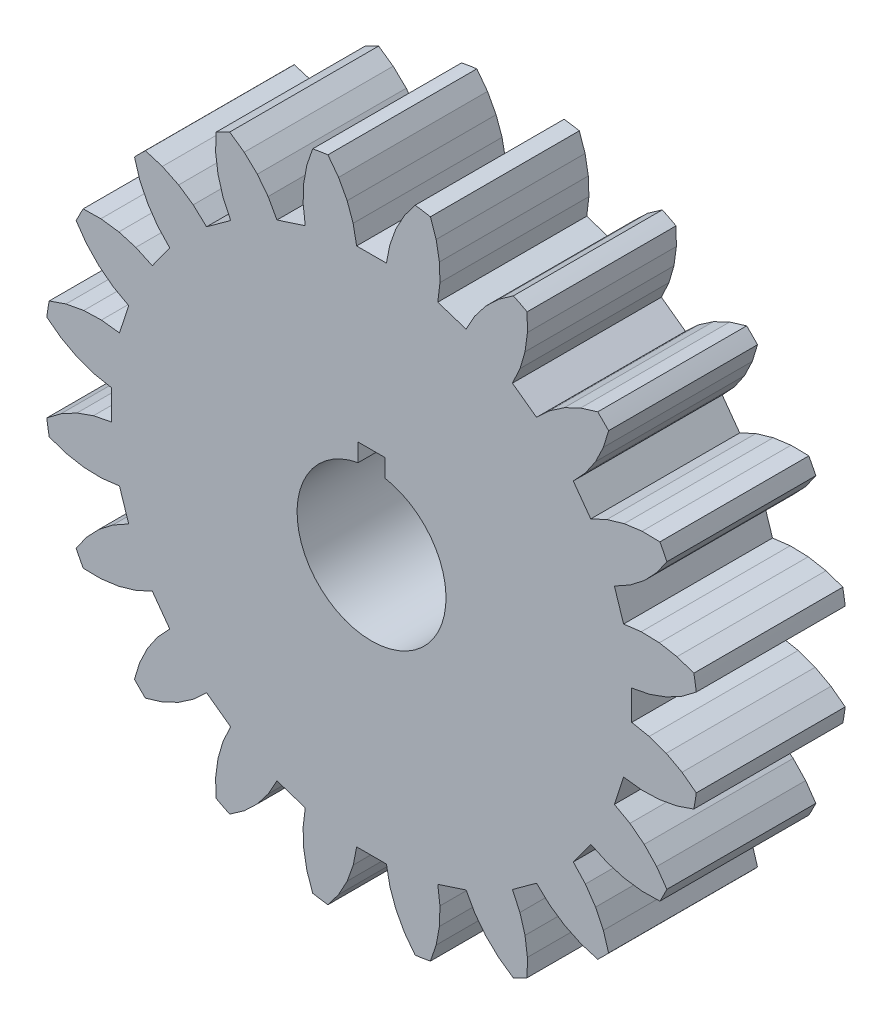
SolidWorks part; units mm, degrees
ref_plane "Alzado" through (0, 0, 0) normal (0, 0, 1) x (1, 0, 0)
ref_plane "Planta" through (0, 0, 0) normal (0, 1, 0) x (1, 0, 0)
ref_plane "Vista lateral" through (0, 0, 0) normal (1, 0, 0) x (0, 0, -1)
sketch "Croquis1" plane through (0, 0, 0) normal (0, 0, 1) x (1, 0, 0)
  line L0 (-0.4418, 0.3705) -> (-0.4418, 2.8705) construction
  line L3 (-0.8918, 2.8297) -> (-0.8918, 3.4297)
  line L4 (-0.8918, 3.4297) -> (0.0082, 3.4297)
  line L5 (0.0082, 2.8297) -> (0.0082, 3.4297)
  arc A0 (-0.8918, 2.8297) -> (0.0082, 2.8297) centre (-0.4418, 0.3705) ccw
  circle A1 centre (-0.4418, 0.3705) radius 11
  point P7 (5.5386, 6.7727)
  point P9 (5.5386, 6.7727)
  dimension "D1" = 5
  dimension "D2" = 0.9
  dimension "D3" = 0.6
extrude "Saliente-Extruir1" add sketch "Croquis1" along normal blind 5
sketch "Croquis6" plane through (0, 0, 5) normal (0, 0, 1) x (1, 0, 0)
  line L0 (6.3309, 5.9091) -> (6.9186, 5.1002)
  line L1 (6.9186, 5.1002) -> (7.4601, 5.3523)
  line L2 (7.4601, 5.3523) -> (8.0415, 5.5228)
  line L3 (8.0415, 5.5228) -> (8.6403, 5.6034)
  line L4 (8.6403, 5.6034) -> (9.2392, 5.5934)
  line L5 (9.2392, 5.5934) -> (8.9398, 6.6146)
  line L6 (8.9398, 6.6146) -> (8.3409, 7.4389)
  line L7 (8.3409, 7.4389) -> (7.5171, 7.9637)
  line L8 (7.5171, 7.9637) -> (7.3429, 7.3946)
  line L9 (7.3429, 7.3946) -> (7.0798, 6.8464)
  line L10 (7.0798, 6.8464) -> (6.7466, 6.3569)
  line L11 (6.7466, 6.3569) -> (6.3309, 5.9091)
  line L12 (8.2447, 3.8426) -> (7.7109, 3.5451)
  line L13 (8.7128, 4.2052) -> (8.2447, 3.8426)
  line L14 (9.1324, 4.6452) -> (8.7128, 4.2052)
  line L15 (9.474, 5.1327) -> (9.1324, 4.6452)
  line L16 (10.0953, 4.3789) -> (9.474, 5.1327)
  line L17 (9.8129, 2.5407) -> (10.3793, 2.3462)
  line L18 (9.2184, 2.6491) -> (9.8129, 2.5407)
  line L19 (8.6128, 2.6667) -> (9.2184, 2.6491)
  line L20 (8.0199, 2.5942) -> (8.6128, 2.6667)
  line L21 (7.7109, 3.5451) -> (8.0199, 2.5942)
  line L22 (10.3793, 2.3462) -> (10.4101, 3.41)
  line L23 (10.4101, 3.41) -> (10.0953, 4.3789)
  line L24 (8.8924, 0.9884) -> (8.2929, 0.8704)
  line L25 (9.4498, 1.1886) -> (8.8924, 0.9884)
  line L26 (9.9848, 1.4774) -> (9.4498, 1.1886)
  line L27 (10.4602, 1.8355) -> (9.9848, 1.4774)
  line L28 (10.8183, 0.9266) -> (10.4602, 1.8355)
  line L29 (9.9816, -0.7343) -> (10.4602, -1.0945)
  line L30 (9.4498, -0.4476) -> (9.9816, -0.7343)
  line L31 (8.8792, -0.2437) -> (9.4498, -0.4476)
  line L32 (8.2929, -0.1294) -> (8.8792, -0.2437)
  line L33 (8.2929, 0.8704) -> (8.2929, -0.1294)
  line L34 (10.4602, -1.0945) -> (10.8183, -0.0922)
  line L35 (10.8183, -0.0922) -> (10.8183, 0.9266)
  line L36 (8.6265, -1.9263) -> (8.0199, -1.8532)
  line L37 (9.2184, -1.9081) -> (8.6265, -1.9263)
  line L38 (9.8165, -1.7988) -> (9.2184, -1.9081)
  line L39 (10.3793, -1.6052) -> (9.8165, -1.7988)
  line L40 (10.439, -2.5802) -> (10.3793, -1.6052)
  line L41 (9.13, -3.9013) -> (9.474, -4.3917)
  line L42 (8.7128, -3.4642) -> (9.13, -3.9013)
  line L43 (8.2332, -3.094) -> (8.7128, -3.4642)
  line L44 (7.7109, -2.8041) -> (8.2332, -3.094)
  line L45 (8.0199, -1.8532) -> (7.7109, -2.8041)
  line L46 (9.474, -4.3917) -> (10.1242, -3.5491)
  line L47 (10.1242, -3.5491) -> (10.439, -2.5802)
  line L48 (7.4729, -4.6161) -> (6.9186, -4.3592)
  line L49 (8.0415, -4.7818) -> (7.4729, -4.6161)
  line L50 (8.6441, -4.8626) -> (8.0415, -4.7818)
  line L51 (9.2392, -4.8524) -> (8.6441, -4.8626)
  line L52 (8.9947, -5.7981) -> (9.2392, -4.8524)
  line L53 (7.3415, -6.6501) -> (7.5171, -7.2227)
  line L54 (7.0798, -6.1054) -> (7.3415, -6.6501)
  line L55 (6.738, -5.6052) -> (7.0798, -6.1054)
  line L56 (6.3309, -5.1681) -> (6.738, -5.6052)
  line L57 (6.9186, -4.3592) -> (6.3309, -5.1681)
  line L58 (7.5171, -7.2227) -> (8.3958, -6.6223)
  line L59 (8.3958, -6.6223) -> (8.9947, -5.7981)
  line L60 (5.5446, -6.8179) -> (5.0968, -6.4022)
  line L61 (6.0342, -7.1511) -> (5.5446, -6.8179)
  line L62 (6.5823, -7.4142) -> (6.0342, -7.1511)
  line L63 (7.1514, -7.5883) -> (6.5823, -7.4142)
  line L64 (6.6266, -8.4122) -> (7.1514, -7.5883)
  line L65 (4.7911, -8.7116) -> (4.7811, -9.3105)
  line L66 (4.7105, -8.1128) -> (4.7911, -8.7116)
  line L67 (4.54, -7.5314) -> (4.7105, -8.1128)
  line L68 (4.2879, -6.9899) -> (4.54, -7.5314)
  line L69 (5.0968, -6.4022) -> (4.2879, -6.9899)
  line L70 (4.7811, -9.3105) -> (5.8024, -9.0111)
  line L71 (5.8024, -9.0111) -> (6.6266, -8.4122)
  line L72 (3.0303, -8.3159) -> (2.7328, -7.7822)
  line L73 (3.3929, -8.7841) -> (3.0303, -8.3159)
  line L74 (3.8329, -9.2037) -> (3.3929, -8.7841)
  line L75 (4.3204, -9.5452) -> (3.8329, -9.2037)
  line L76 (3.5667, -10.1666) -> (4.3204, -9.5452)
  line L77 (1.7285, -9.8842) -> (1.5339, -10.4506)
  line L78 (1.8369, -9.2897) -> (1.7285, -9.8842)
  line L79 (1.8544, -8.6841) -> (1.8369, -9.2897)
  line L80 (1.7819, -8.0912) -> (1.8544, -8.6841)
  line L81 (2.7328, -7.7822) -> (1.7819, -8.0912)
  line L82 (1.5339, -10.4506) -> (2.5977, -10.4814)
  line L83 (2.5977, -10.4814) -> (3.5667, -10.1666)
  line L84 (0.1761, -8.9637) -> (0.0581, -8.3642)
  line L85 (0.3763, -9.5211) -> (0.1761, -8.9637)
  line L86 (0.6651, -10.0561) -> (0.3763, -9.5211)
  line L87 (1.0232, -10.5315) -> (0.6651, -10.0561)
  line L88 (0.1143, -10.8895) -> (1.0232, -10.5315)
  line L89 (-1.5466, -10.0529) -> (-1.9067, -10.5315)
  line L90 (-1.2598, -9.5211) -> (-1.5466, -10.0529)
  line L91 (-1.056, -8.9505) -> (-1.2598, -9.5211)
  line L92 (-0.9417, -8.3642) -> (-1.056, -8.9505)
  line L93 (0.0581, -8.3642) -> (-0.9417, -8.3642)
  line L94 (-1.9067, -10.5315) -> (-0.9045, -10.8895)
  line L95 (-0.9045, -10.8895) -> (0.1143, -10.8895)
  line L96 (-2.7386, -8.6978) -> (-2.6655, -8.0912)
  line L97 (-2.7204, -9.2897) -> (-2.7386, -8.6978)
  line L98 (-2.6111, -9.8878) -> (-2.7204, -9.2897)
  line L99 (-2.4174, -10.4506) -> (-2.6111, -9.8878)
  line L100 (-3.3924, -10.5103) -> (-2.4174, -10.4506)
  line L101 (-4.7136, -9.2013) -> (-5.2039, -9.5452)
  line L102 (-4.2765, -8.7841) -> (-4.7136, -9.2013)
  line L103 (-3.9063, -8.3045) -> (-4.2765, -8.7841)
  line L104 (-3.6164, -7.7822) -> (-3.9063, -8.3045)
  line L105 (-2.6655, -8.0912) -> (-3.6164, -7.7822)
  line L106 (-5.2039, -9.5452) -> (-4.3614, -10.1955)
  line L107 (-4.3614, -10.1955) -> (-3.3924, -10.5103)
  line L108 (-5.4284, -7.5442) -> (-5.1715, -6.9899)
  line L109 (-5.5941, -8.1128) -> (-5.4284, -7.5442)
  line L110 (-5.6749, -8.7154) -> (-5.5941, -8.1128)
  line L111 (-5.6647, -9.3105) -> (-5.6749, -8.7154)
  line L112 (-6.6104, -9.0659) -> (-5.6647, -9.3105)
  line L113 (-7.4623, -7.4128) -> (-8.035, -7.5883)
  line L114 (-6.9177, -7.1511) -> (-7.4623, -7.4128)
  line L115 (-6.4175, -6.8093) -> (-6.9177, -7.1511)
  line L116 (-5.9804, -6.4022) -> (-6.4175, -6.8093)
  line L117 (-5.1715, -6.9899) -> (-5.9804, -6.4022)
  line L118 (-8.035, -7.5883) -> (-7.4346, -8.4671)
  line L119 (-7.4346, -8.4671) -> (-6.6104, -9.0659)
  line L120 (-7.6301, -5.6159) -> (-7.2145, -5.1681)
  line L121 (-7.9634, -6.1054) -> (-7.6301, -5.6159)
  line L122 (-8.2265, -6.6536) -> (-7.9634, -6.1054)
  line L123 (-8.4006, -7.2227) -> (-8.2265, -6.6536)
  line L124 (-9.2245, -6.6979) -> (-8.4006, -7.2227)
  line L125 (-9.5239, -4.8624) -> (-10.1228, -4.8524)
  line L126 (-8.9251, -4.7818) -> (-9.5239, -4.8624)
  line L127 (-8.3437, -4.6113) -> (-8.9251, -4.7818)
  line L128 (-7.8022, -4.3592) -> (-8.3437, -4.6113)
  line L129 (-7.2145, -5.1681) -> (-7.8022, -4.3592)
  line L130 (-10.1228, -4.8524) -> (-9.8233, -5.8736)
  line L131 (-9.8233, -5.8736) -> (-9.2245, -6.6979)
  line L132 (-9.1282, -3.1016) -> (-8.5945, -2.8041)
  line L133 (-9.5964, -3.4642) -> (-9.1282, -3.1016)
  line L134 (-10.016, -3.9042) -> (-9.5964, -3.4642)
  line L135 (-10.3575, -4.3917) -> (-10.016, -3.9042)
  line L136 (-10.9789, -3.6379) -> (-10.3575, -4.3917)
  line L137 (-10.6964, -1.7997) -> (-11.2629, -1.6052)
  line L138 (-10.102, -1.9081) -> (-10.6964, -1.7997)
  line L139 (-9.4964, -1.9257) -> (-10.102, -1.9081)
  line L140 (-8.9035, -1.8532) -> (-9.4964, -1.9257)
  line L141 (-8.5945, -2.8041) -> (-8.9035, -1.8532)
  line L142 (-11.2629, -1.6052) -> (-11.2937, -2.669)
  line L143 (-11.2937, -2.669) -> (-10.9789, -3.6379)
  line L144 (-9.776, -0.2474) -> (-9.1765, -0.1294)
  line L145 (-10.3333, -0.4476) -> (-9.776, -0.2474)
  line L146 (-10.8684, -0.7364) -> (-10.3333, -0.4476)
  line L147 (-11.3438, -1.0945) -> (-10.8684, -0.7364)
  line L148 (-11.7018, -0.1856) -> (-11.3438, -1.0945)
  line L149 (-10.8652, 1.4753) -> (-11.3438, 1.8355)
  line L150 (-10.3333, 1.1886) -> (-10.8652, 1.4753)
  line L151 (-9.7628, 0.9847) -> (-10.3333, 1.1886)
  line L152 (-9.1765, 0.8704) -> (-9.7628, 0.9847)
  line L153 (-9.1765, -0.1294) -> (-9.1765, 0.8704)
  line L154 (-11.3438, 1.8355) -> (-11.7018, 0.8332)
  line L155 (-11.7018, 0.8332) -> (-11.7018, -0.1856)
  line L156 (-9.5101, 2.6673) -> (-8.9035, 2.5942)
  line L157 (-10.102, 2.6491) -> (-9.5101, 2.6673)
  line L158 (-10.7001, 2.5398) -> (-10.102, 2.6491)
  line L159 (-11.2629, 2.3462) -> (-10.7001, 2.5398)
  line L160 (-11.3226, 3.3212) -> (-11.2629, 2.3462)
  line L161 (-10.0136, 4.6423) -> (-10.3575, 5.1327)
  line L162 (-9.5964, 4.2052) -> (-10.0136, 4.6423)
  line L163 (-9.1168, 3.835) -> (-9.5964, 4.2052)
  line L164 (-8.5945, 3.5451) -> (-9.1168, 3.835)
  line L165 (-8.9035, 2.5942) -> (-8.5945, 3.5451)
  line L166 (-10.3575, 5.1327) -> (-11.0077, 4.2901)
  line L167 (-11.0077, 4.2901) -> (-11.3226, 3.3212)
  line L168 (-8.3565, 5.3571) -> (-7.8022, 5.1002)
  line L169 (-8.9251, 5.5228) -> (-8.3565, 5.3571)
  line L170 (-9.5277, 5.6036) -> (-8.9251, 5.5228)
  line L171 (-10.1228, 5.5934) -> (-9.5277, 5.6036)
  line L172 (-9.8782, 6.5391) -> (-10.1228, 5.5934)
  line L173 (-8.2251, 7.3911) -> (-8.4006, 7.9637)
  line L174 (-7.9634, 6.8464) -> (-8.2251, 7.3911)
  line L175 (-7.6216, 6.3462) -> (-7.9634, 6.8464)
  line L176 (-7.2145, 5.9091) -> (-7.6216, 6.3462)
  line L177 (-7.8022, 5.1002) -> (-7.2145, 5.9091)
  line L178 (-8.4006, 7.9637) -> (-9.2794, 7.3633)
  line L179 (-9.2794, 7.3633) -> (-9.8782, 6.5391)
  line L180 (-6.4282, 7.5589) -> (-5.9804, 7.1432)
  line L181 (-6.9177, 7.8921) -> (-6.4282, 7.5589)
  line L182 (-7.4659, 8.1552) -> (-6.9177, 7.8921)
  line L183 (-8.035, 8.3293) -> (-7.4659, 8.1552)
  line L184 (-7.5102, 9.1532) -> (-8.035, 8.3293)
  line L185 (-5.6747, 9.4526) -> (-5.6647, 10.0515)
  line L186 (-5.5941, 8.8538) -> (-5.6747, 9.4526)
  line L187 (-5.4236, 8.2724) -> (-5.5941, 8.8538)
  line L188 (-5.1715, 7.7309) -> (-5.4236, 8.2724)
  line L189 (-5.9804, 7.1432) -> (-5.1715, 7.7309)
  line L190 (-5.6647, 10.0515) -> (-6.6859, 9.7521)
  line L191 (-6.6859, 9.7521) -> (-7.5102, 9.1532)
  line L192 (-3.9139, 9.0569) -> (-3.6164, 8.5232)
  line L193 (-4.2765, 9.5251) -> (-3.9139, 9.0569)
  line L194 (-4.7165, 9.9447) -> (-4.2765, 9.5251)
  line L195 (-5.2039, 10.2862) -> (-4.7165, 9.9447)
  line L196 (-4.4502, 10.9076) -> (-5.2039, 10.2862)
  line L197 (-2.612, 10.6252) -> (-2.4174, 11.1916)
  line L198 (-2.7204, 10.0307) -> (-2.612, 10.6252)
  line L199 (-2.738, 9.4251) -> (-2.7204, 10.0307)
  line L200 (-2.6655, 8.8322) -> (-2.738, 9.4251)
  line L201 (-3.6164, 8.5232) -> (-2.6655, 8.8322)
  line L202 (-2.4174, 11.1916) -> (-3.4812, 11.2224)
  line L203 (-3.4812, 11.2224) -> (-4.4502, 10.9076)
  line L204 (-1.0597, 9.7047) -> (-0.9417, 9.1052)
  line L205 (-1.2598, 10.2621) -> (-1.0597, 9.7047)
  line L206 (-1.5487, 10.7971) -> (-1.2598, 10.2621)
  line L207 (-1.9067, 11.2725) -> (-1.5487, 10.7971)
  line L208 (-0.9979, 11.6305) -> (-1.9067, 11.2725)
  line L209 (0.6631, 10.7939) -> (1.0232, 11.2725)
  line L210 (0.3763, 10.2621) -> (0.6631, 10.7939)
  line L211 (0.1725, 9.6915) -> (0.3763, 10.2621)
  line L212 (0.0581, 9.1052) -> (0.1725, 9.6915)
  line L213 (-0.9417, 9.1052) -> (0.0581, 9.1052)
  line L214 (1.0232, 11.2725) -> (0.0209, 11.6305)
  line L215 (0.0209, 11.6305) -> (-0.9979, 11.6305)
  line L216 (1.855, 9.4388) -> (1.7819, 8.8322)
  line L217 (1.8369, 10.0307) -> (1.855, 9.4388)
  line L218 (1.7275, 10.6288) -> (1.8369, 10.0307)
  line L219 (1.5339, 11.1916) -> (1.7275, 10.6288)
  line L220 (2.5089, 11.2513) -> (1.5339, 11.1916)
  line L221 (3.83, 9.9423) -> (4.3204, 10.2862)
  line L222 (3.3929, 9.5251) -> (3.83, 9.9423)
  line L223 (3.0228, 9.0455) -> (3.3929, 9.5251)
  line L224 (2.7328, 8.5232) -> (3.0228, 9.0455)
  line L225 (1.7819, 8.8322) -> (2.7328, 8.5232)
  line L226 (4.3204, 10.2862) -> (3.4778, 10.9365)
  line L227 (3.4778, 10.9365) -> (2.5089, 11.2513)
  line L228 (4.5449, 8.2852) -> (4.2879, 7.7309)
  line L229 (4.7105, 8.8538) -> (4.5449, 8.2852)
  line L230 (4.7913, 9.4564) -> (4.7105, 8.8538)
  line L231 (4.7811, 10.0515) -> (4.7913, 9.4564)
  line L232 (5.7268, 9.8069) -> (4.7811, 10.0515)
  line L233 (6.5788, 8.1538) -> (7.1514, 8.3293)
  line L234 (6.0342, 7.8921) -> (6.5788, 8.1538)
  line L235 (5.5339, 7.5503) -> (6.0342, 7.8921)
  line L236 (5.0968, 7.1432) -> (5.5339, 7.5503)
  line L237 (4.2879, 7.7309) -> (5.0968, 7.1432)
  line L238 (7.1514, 8.3293) -> (6.5511, 9.2081)
  line L239 (6.5511, 9.2081) -> (5.7268, 9.8069)
  circle A1 centre (-0.4418, 0.3705) radius 11 construction
  point P253 (-0.4418, 0.3705)
  dimension "D1" = 20
extrude "Cortar-Extruir6" cut sketch "Croquis6" against normal blind 5
